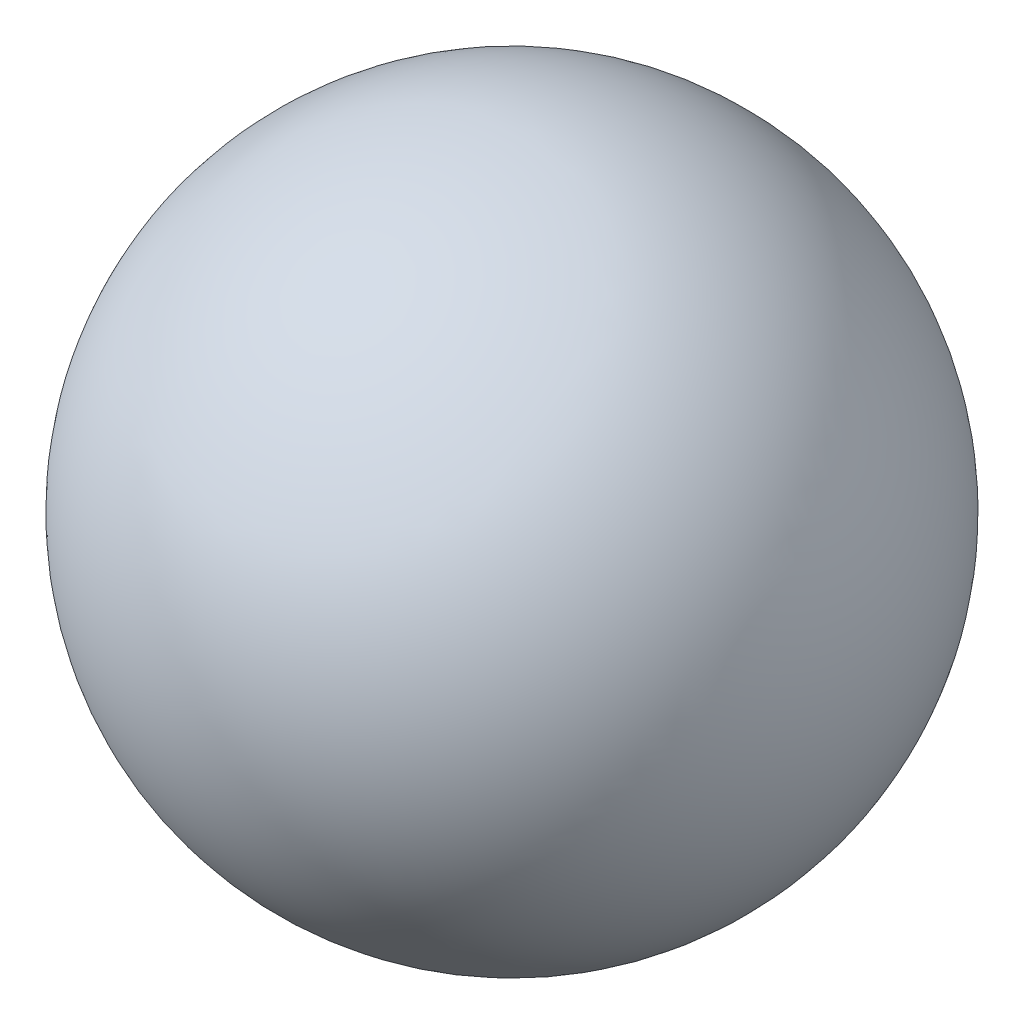
SolidWorks part; units mm, degrees
ref_plane "Front Plane" through (0, 0, 0) normal (0, 0, 1) x (1, 0, 0)
ref_plane "Top Plane" through (0, 0, 0) normal (0, 1, 0) x (1, 0, 0)
ref_plane "Right Plane" through (0, 0, 0) normal (1, 0, 0) x (0, 0, -1)
sketch "Sketch1" plane through (0, 0, 0) normal (0, 0, 1) x (1, 0, 0)
  line L0 (-30, 0) -> (30, 0)
  arc A0 (-30, 0) -> (30, 0) centre (0, 0) ccw
revolve "Revolve1" add sketch "Sketch1" angle 360 about L0
